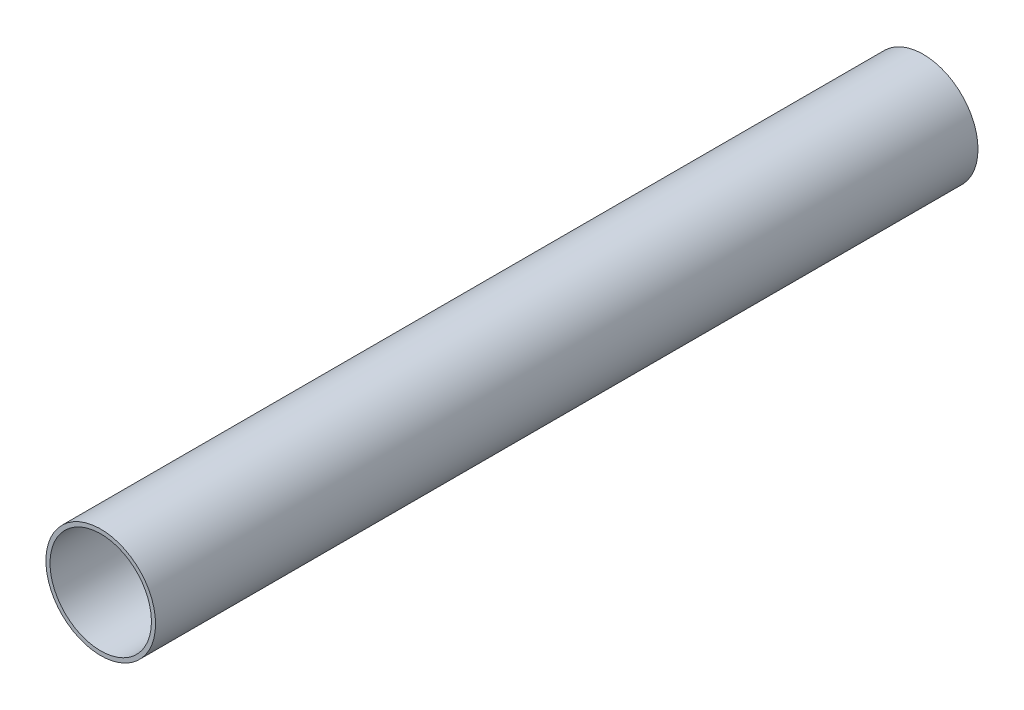
SolidWorks part; units mm, degrees
ref_plane "Front Plane" through (0, 0, 0) normal (0, 0, 1) x (1, 0, 0)
ref_plane "Top Plane" through (0, 0, 0) normal (0, 1, 0) x (1, 0, 0)
ref_plane "Right Plane" through (0, 0, 0) normal (1, 0, 0) x (0, 0, -1)
sketch "Sketch1" plane through (0, 0, 0) normal (0, 0, 1) x (1, 0, 0)
  circle A2 centre (0, 0) radius 18.5
  circle A3 centre (0, 0) radius 20
  point P2 (0, 0)
  dimension "D1" = 40
  dimension "D2" = 37
extrude "Boss-Extrude1" add sketch "Sketch1" along normal mid plane 300
